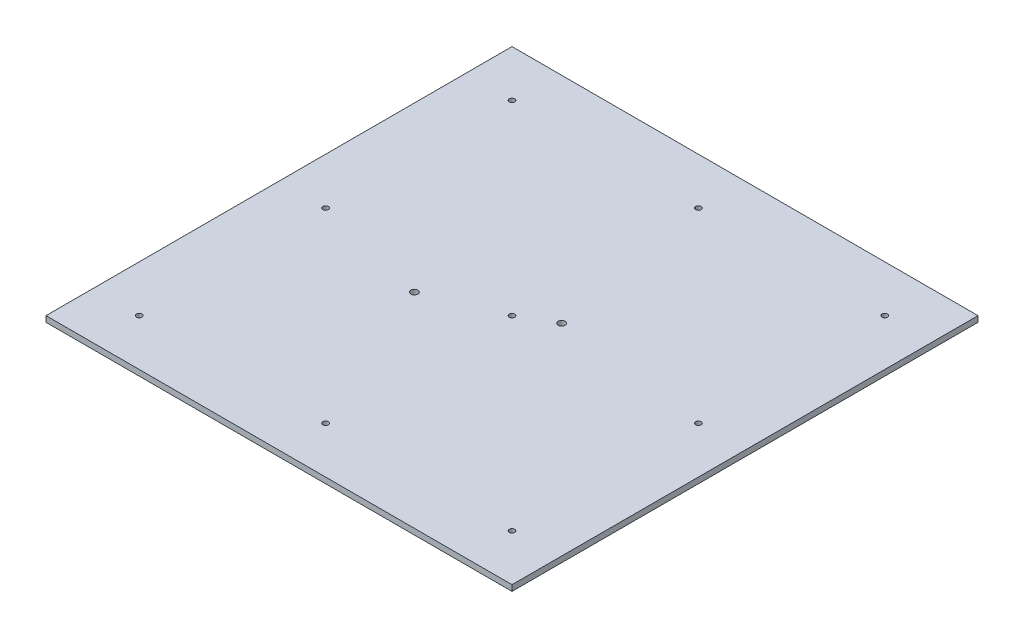
SolidWorks part; units mm, degrees
ref_plane "Front Plane" through (0, 0, 0) normal (0, 0, 1) x (1, 0, 0)
ref_plane "Top Plane" through (0, 0, 0) normal (0, 1, 0) x (1, 0, 0)
ref_plane "Right Plane" through (0, 0, 0) normal (1, 0, 0) x (0, 0, -1)
sketch "Sketch1" plane through (0, 0, 0) normal (0, 1, 0) x (1, 0, 0)
  line L1 (127, 127) -> (-127, 127)
  line L2 (127, 127) -> (127, -127)
  line L3 (127, -127) -> (-127, -127)
  line L4 (-127, 127) -> (-127, -127)
  line L5 (127, 127) -> (-127, -127) construction
  line L6 (127, -127) -> (-127, 127) construction
  point P0 (0, 0)
  dimension "D1" = 254
  dimension "D2" = 254
extrude "Boss-Extrude1" add sketch "Sketch1" along normal blind 3.175
sketch "Sketch2" plane through (0, 3.175, 0) normal (0, 1, 0) x (1, 0, 0)
  line L0 (0, 101.6) -> (0, -101.6)
  line L1 (101.6, -101.6) -> (-101.6, -101.6)
  line L2 (101.6, -101.6) -> (101.6, 101.6)
  line L3 (101.6, 101.6) -> (-101.6, 101.6)
  line L4 (-101.6, -101.6) -> (-101.6, 101.6)
  line L5 (101.6, -101.6) -> (-101.6, 101.6) construction
  line L6 (101.6, 101.6) -> (-101.6, -101.6) construction
  line L9 (-101.6, 0) -> (101.6, 0)
  point P0 (0, 0)
  dimension "D1" = 203.2
  dimension "D2" = 203.2
hole_wizard "Ø3.0mm Dowel Hole1" positions "3DSketch2" profile "Sketch4" hole size "Ø3.0" standard "ANSI Metric" end condition through all
sketch3d "3DSketch2"
  point P0 (0, 3.175, 0)
  point P3 (-101.6, 3.175, 0)
  point P6 (101.6, 3.175, 0)
  point P9 (101.6, 3.175, 101.6)
  point P12 (0, 3.175, 101.6)
  point P15 (-101.6, 3.175, 101.6)
  point P18 (-101.6, 3.175, -101.6)
  point P21 (0, 3.175, -101.6)
  point P24 (101.6, 3.175, -101.6)
sketch "Sketch4" plane through (0, 3.175, 0) normal (1, 0, 0) x (0, 0, 1)
  line L0 (0, 0) -> (0, 3.175)
  line L1 (0, 3.175) -> (1.5, 3.175)
  line L2 (1.5, 3.175) -> (1.5, 0)
  line L5 (1.5, 0) -> (0, 0)
  line L11 (0, -6.35) -> (0, 107.95) construction
  dimension "Thru Hole Dia." = 3
  dimension "Thru Hole Depth" = 3.175
sketch "Sketch5" plane through (0, 3.175, 0) normal (0, 1, 0) x (1, 0, 0)
  line L0 (-37.719, -27.94) -> (-37.719, -15.494)
  line L1 (-42.545, 27.94) -> (42.545, 27.94)
  line L2 (-42.545, 27.94) -> (-42.545, -27.94)
  line L3 (-42.545, -27.94) -> (42.545, -27.94)
  line L4 (42.545, 27.94) -> (42.545, -27.94)
  line L5 (-42.545, 27.94) -> (42.545, -27.94) construction
  line L6 (-42.545, -27.94) -> (42.545, 27.94) construction
  line L7 (-37.719, -15.494) -> (-42.545, -15.494)
  line L8 (17.145, 27.94) -> (17.145, -27.94)
  line L9 (17.145, 9.906) -> (42.545, 9.906)
  circle A1 centre (17.145, 9.906) radius 1.905
  circle A2 centre (-37.719, -15.494) radius 1.905
  point P0 (0, 0)
  dimension "D7" = 3.81
  dimension "D8" = 3.81
  dimension "D1" = 85.09
  dimension "D2" = 55.88
  dimension "D3" = 4.826
  dimension "D4" = 12.446
  dimension "D5" = 25.4
  dimension "D6" = 18.034
extrude "Cut-Extrude1" cut sketch "Sketch5" against normal through all contours L8 A1 | L8 A1 L9 | L9 A1 L8 | L0 A2 L7 | L7 A2 L0
